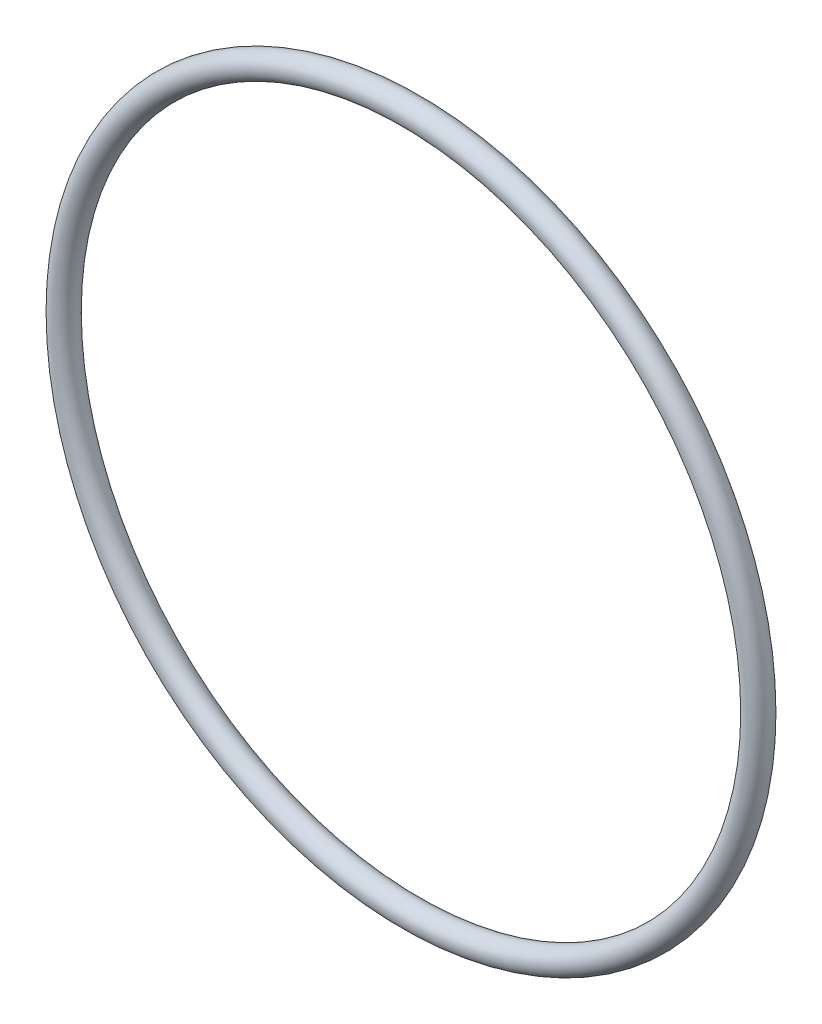
SolidWorks part; units mm, degrees
ref_plane "Front" through (0, 0, 0) normal (0, 0, 1) x (1, 0, 0)
ref_plane "Top" through (0, 0, 0) normal (0, 1, 0) x (1, 0, 0)
ref_plane "Right" through (0, 0, 0) normal (1, 0, 0) x (0, 0, -1)
sketch "Sketch1" plane through (0, 0, 0) normal (1, 0, 0) x (0, -1, 0)
  line L0 (0, -1.7653) -> (0, 1.7653) construction
  line L2 (-56.0476, 0) -> (56.0476, 0) construction
  line L3 (-47.4218, 0) -> (47.4218, 0) construction
  circle A0 centre (49.1871, 0) radius 1.7653
  point P9 (47.4218, 0)
  point P10 (50.9524, 0)
  point P13 (49.1871, 1.7653)
  point P14 (49.1871, -1.7653)
  dimension "Width" = 3.5306
  dimension "ID" = 94.8436
revolve "Revolve1" add sketch "Sketch1" angle 360 about L0
